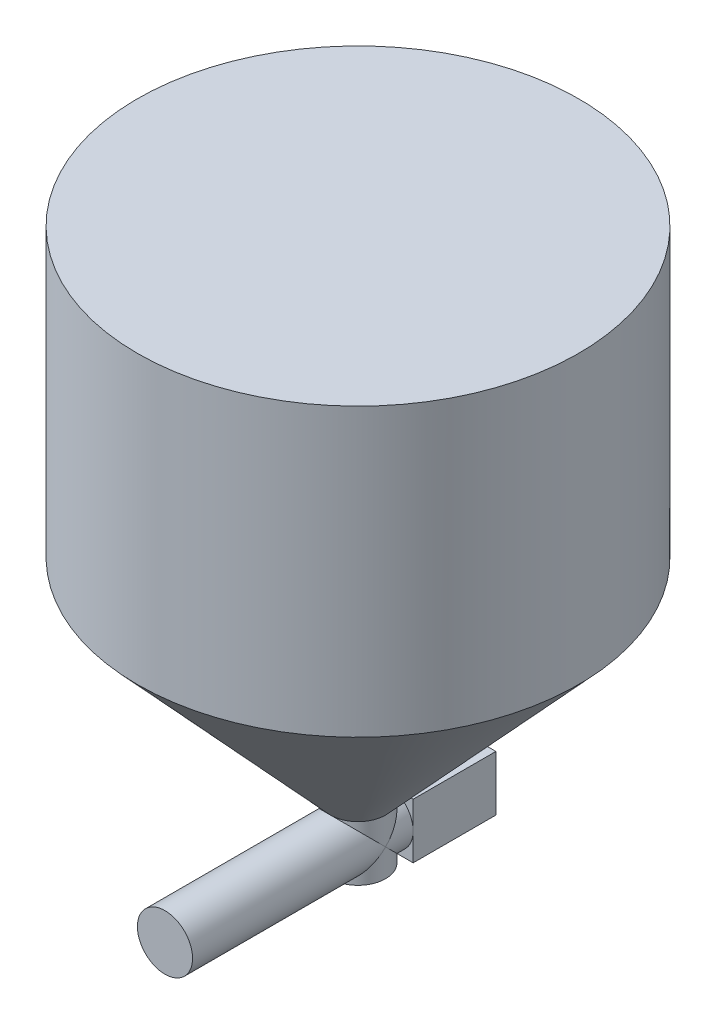
SolidWorks part; units mm, degrees
ref_plane "Alzado" through (0, 0, 0) normal (0, 0, 1) x (1, 0, 0)
ref_plane "Planta" through (0, 0, 0) normal (0, 1, 0) x (1, 0, 0)
ref_plane "Vista lateral" through (0, 0, 0) normal (1, 0, 0) x (0, 0, -1)
sketch "Croquis1" plane through (0, 0, 0) normal (0, 1, 0) x (1, 0, 0)
  circle A0 centre (0, 0) radius 400
  dimension "D1" = 800
ref_plane "Plano1" through (0, -900, 0) normal (0, 1, 0) x (1, 0, 0)
extrude "Saliente-Extruir1" add sketch "Croquis1" against normal blind 520 contours A0
sketch "Croquis2" plane through (0, -520, 0) normal (0, -1, 0) x (1, 0, 0)
  circle A0 centre (0, 0) radius 400
  dimension "D1" = 800
sketch "Croquis3" plane through (0, -900, 0) normal (0, 1, 0) x (1, 0, 0)
  circle A0 centre (0, 0) radius 50
  dimension "D1" = 100
loft "Recubrir1" add profiles "Croquis3", "Croquis2"
sketch "Croquis4" plane through (0, -900, 0) normal (0, -1, 0) x (1, 0, 0)
  circle A0 centre (0, 0) radius 50
extrude "Saliente-Extruir2" add sketch "Croquis4" along normal blind 100
ref_plane "Plano2" through (0, 0, -50) normal (0, 0, -1) x (-1, 0, 0)
sketch "Croquis5" plane through (0, 0, -50) normal (0, 0, -1) x (-1, 0, 0)
  line L0 (-50, -1000) -> (50, -1000) construction
  line L3 (0, -1000) -> (0, -900) construction
  line L4 (440, -900) -> (-440, -900) construction
  circle A0 centre (0, -950) radius 50
extrude "Saliente-Extruir3" add sketch "Croquis5" against normal blind 400
sketch "Croquis6" plane through (0, 0, -50) normal (0, 0, -1) x (-1, 0, 0)
  line L0 (-50, -950) -> (50, -950) construction
  line L2 (-50, -900) -> (50, -900)
  line L3 (-50, -900) -> (-50, -1000)
  line L4 (-50, -1000) -> (50, -1000)
  line L5 (50, -900) -> (50, -1000)
  line L6 (-50, -900) -> (50, -1000) construction
  line L7 (-50, -1000) -> (50, -900) construction
  arc A0 (0, -900) -> (0, -1000) centre (0, -950) ccw construction
  arc A1 (0, -1000) -> (0, -900) centre (0, -950) ccw construction
  point P8 (0, -950)
  dimension "D1" = 100
  dimension "D2" = 100
extrude "Saliente-Extruir4" add sketch "Croquis6" along normal blind 150
